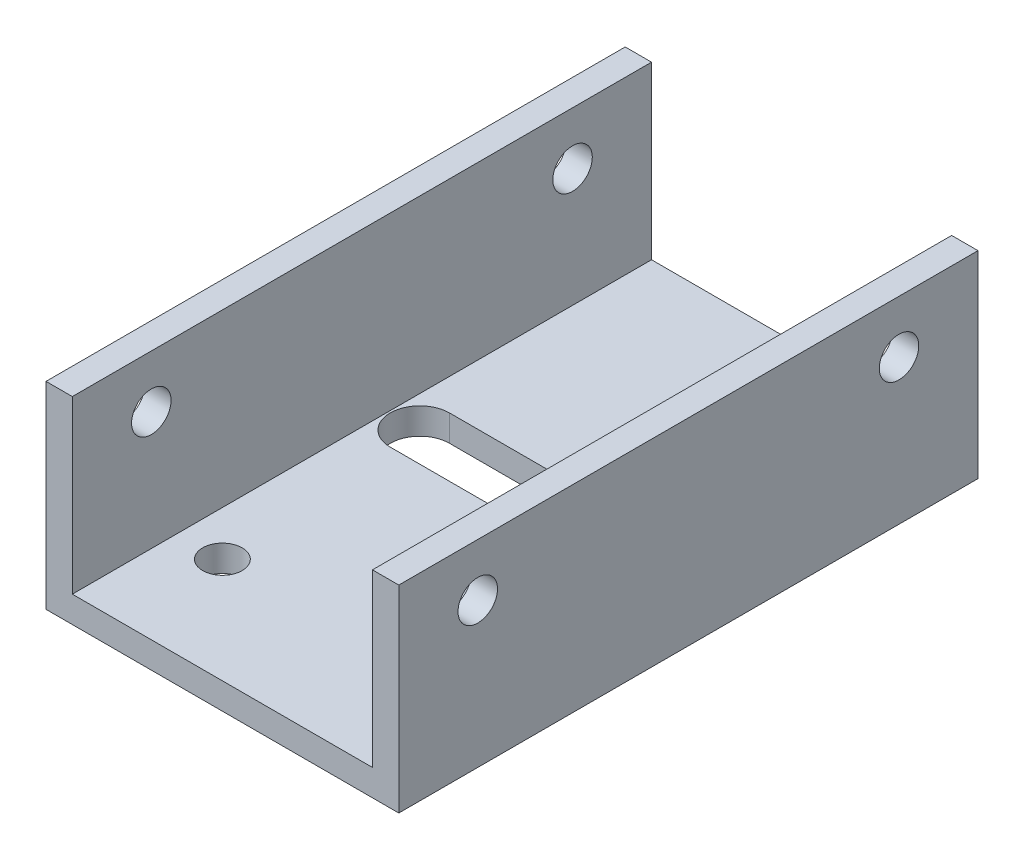
SolidWorks part; units mm, degrees
ref_plane "Front Plane" through (0, 0, 0) normal (0, 0, 1) x (1, 0, 0)
ref_plane "Top Plane" through (0, 0, 0) normal (0, 1, 0) x (1, 0, 0)
ref_plane "Right Plane" through (0, 0, 0) normal (1, 0, 0) x (0, 0, -1)
sketch "Sketch2" plane through (0, 0, 0) normal (0, 0, 1) x (1, 0, 0)
  line L0 (24.8, 15) -> (26.8, 15)
  line L1 (0, 0) -> (26.8, 0)
  line L2 (0, 0) -> (0, 15)
  line L3 (0, 15) -> (2, 15)
  line L4 (26.8, 0) -> (26.8, 15)
  line L6 (2, 15) -> (2, 2)
  line L7 (2, 2) -> (24.8, 2)
  line L8 (24.8, 15) -> (24.8, 2)
  dimension "D1" = 2
  dimension "D2" = 15
  dimension "D3" = 2
  dimension "D4" = 26.8
extrude "Boss-Extrude1" add sketch "Sketch2" along normal blind 44
fillet "Fillet1" [suppressed] radius 2
sketch "Sketch3" plane through (0, 0, 0) normal (0, -1, 0) x (1, 0, 0)
  line L0 (0, 44) -> (26.8, 44) construction
  line L1 (0, 0) -> (26.8, 0) construction
  line L2 (5.4, 36) -> (21.4, 36)
  line L3 (2, 44) -> (2, 0) construction
  line L4 (0, 44) -> (0, 0) construction
  line L5 (24.8, 44) -> (24.8, 0) construction
  line L6 (22.4, 17.75) -> (4.4, 17.75)
  line L7 (22.4, 22.25) -> (4.4, 22.25)
  line L8 (26.8, 44) -> (26.8, 0) construction
  circle A0 centre (21.4, 36) radius 1.5
  circle A1 centre (13.4, 8) radius 1.5
  circle A2 centre (5.4, 36) radius 1.5
  arc A3 (4.4, 22.25) -> (4.4, 17.75) centre (4.4, 20) ccw
  arc A4 (22.4, 17.75) -> (22.4, 22.25) centre (22.4, 20) ccw
  point P22 (0, 0)
  dimension "D1" = 3
  dimension "D7" = 4.5
  dimension "D8" = 8
  dimension "D2" = 16
  dimension "D3" = 8
  dimension "D4" = 3.4
  dimension "D5" = 20
  dimension "D6" = 4.4
  dimension "D9" = 13.4
  dimension "D10" = 3.4
  dimension "D11" = 4.4
  dimension "D12" = 18
  dimension "D13" = 13.4
extrude "Cut-Extrude1" cut sketch "Sketch3" against normal blind 30
sketch "Sketch4" plane through (0, 0, 0) normal (-1, 0, 0) x (0, 0, 1)
  line L0 (44, 15) -> (0, 15) construction
  line L1 (0, 15) -> (0, 0) construction
  line L2 (44, 15) -> (44, 0) construction
  circle A0 centre (6, 11) radius 1.5
  circle A1 centre (38, 11) radius 1.5
  dimension "D1" = 3
  dimension "D4" = 6
  dimension "D5" = 6
  dimension "D2" = 4
  dimension "D3" = 4
extrude "Cut-Extrude2" cut sketch "Sketch4" against normal blind 30
